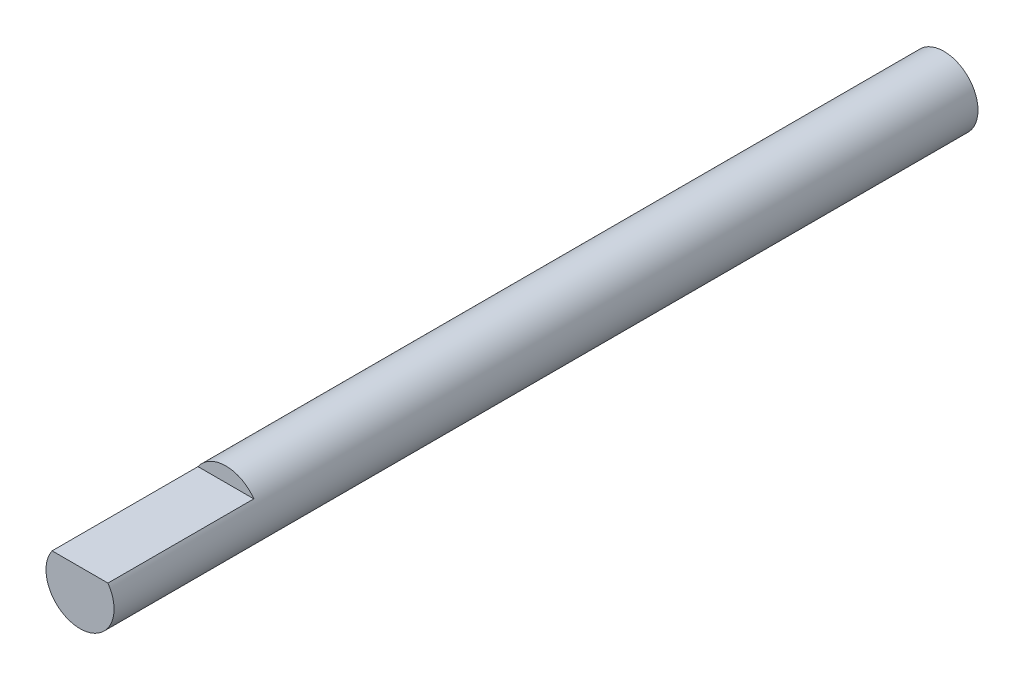
SolidWorks part; units mm, degrees
ref_plane "Płaszczyzna przednia" through (0, 0, 0) normal (0, 0, 1) x (1, 0, 0)
ref_plane "Płaszczyzna górna" through (0, 0, 0) normal (0, 1, 0) x (1, 0, 0)
ref_plane "Płaszczyzna prawa" through (0, 0, 0) normal (1, 0, 0) x (0, 0, -1)
sketch "Szkic1" plane through (0, 0, 0) normal (0, 0, 1) x (1, 0, 0)
  circle A0 centre (0, 0) radius 7
  dimension "D1" = 14
extrude "Dodanie-wyciągnięcie1" add sketch "Szkic1" along normal blind 177.7
sketch "Szkic2" plane through (0, 0, 177.7) normal (0, 0, 1) x (1, 0, 0)
  line L1 (-7, 10) -> (7, 10)
  line L2 (-7, 10) -> (-7, 4)
  line L3 (-7, 4) -> (7, 4)
  line L4 (7, 10) -> (7, 4)
  line L5 (-7, 10) -> (7, 4) construction
  line L6 (-7, 4) -> (7, 10) construction
  circle A0 centre (0, 0) radius 7 construction
  point P0 (0, 7)
  point P7 (0, 0)
  dimension "D1" = 6
  dimension "D2" = 14
extrude "Wytnij-wyciągnięcie1" cut sketch "Szkic2" against normal blind 30
